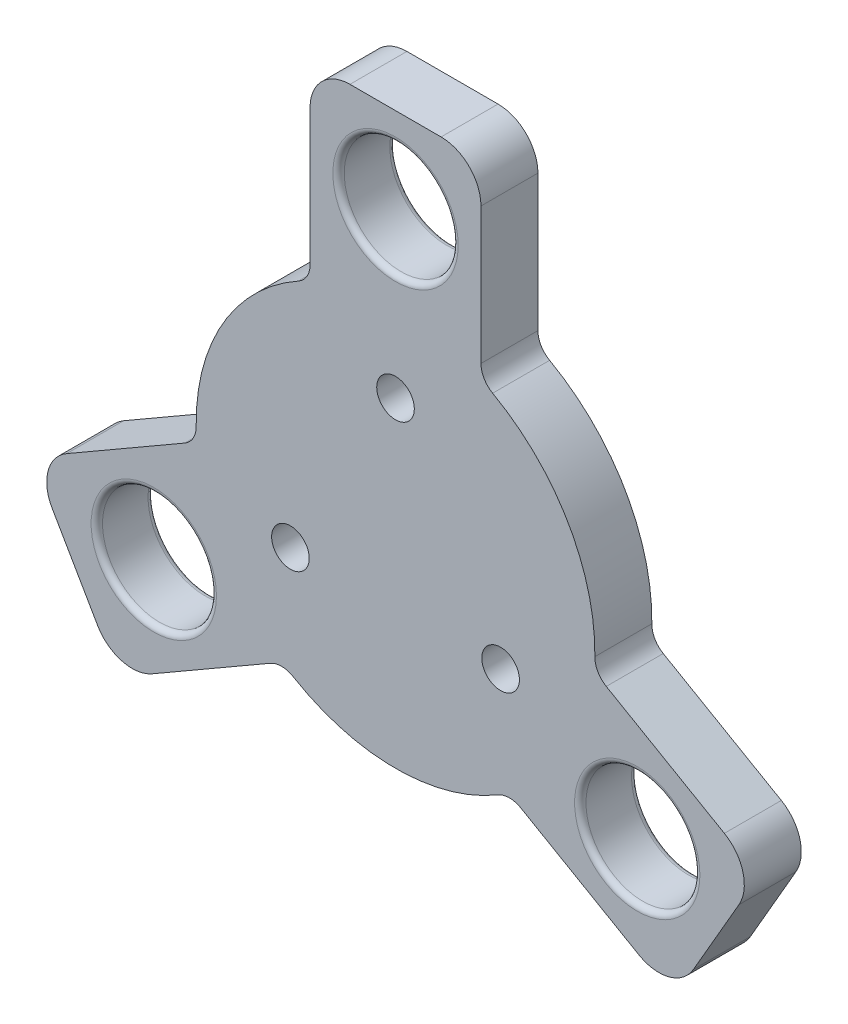
SolidWorks part; units mm, degrees
ref_plane "Front Plane" through (0, 0, 0) normal (0, 0, 1) x (1, 0, 0)
ref_plane "Top Plane" through (0, 0, 0) normal (0, 1, 0) x (1, 0, 0)
ref_plane "Right Plane" through (0, 0, 0) normal (1, 0, 0) x (0, 0, -1)
sketch "Sketch1" plane through (0, 0, 0) normal (0, 0, 1) x (1, 0, 0)
  line L0 (0, 17.5) -> (0, 0) construction
  line L1 (0, 0) -> (-15.1554, -8.75) construction
  line L2 (0, 0) -> (15.1554, -8.75) construction
  line L3 (-7.5, 32.5) -> (-7.5, 15.8114)
  line L4 (7.5, 32.5) -> (7.5, 15.8114)
  line L5 (-7.5, 32.5) -> (7.5, 32.5)
  line L6 (31.8958, -9.7548) -> (17.4431, -1.4105)
  line L7 (24.3958, -22.7452) -> (9.9431, -14.4009)
  line L8 (31.8958, -9.7548) -> (24.3958, -22.7452)
  line L9 (-31.8958, -9.7548) -> (-17.4431, -1.4105)
  line L10 (-24.3958, -22.7452) -> (-9.9431, -14.4009)
  line L11 (-31.8958, -9.7548) -> (-24.3958, -22.7452)
  line L12 (-21.2176, -12.25) -> (-28.1458, -16.25) construction
  line L13 (21.2176, -12.25) -> (28.1458, -16.25) construction
  line L14 (0, 25) -> (0, 30) construction
  line L15 (0, 30) -> (0, 32.5) construction
  circle A0 centre (0, 0) radius 17.5
  circle A1 centre (-21.2176, -12.25) radius 5
  circle A2 centre (21.2176, -12.25) radius 5
  circle A3 centre (0, 25) radius 5
  circle A4 centre (0, 0) radius 2.4
  dimension "D1" = 35
  dimension "D10" = 10
  dimension "D11" = 4.8
  dimension "D2" = 120
  dimension "D3" = 120
  dimension "D4" = 15
  dimension "D5" = 15
  dimension "D12" = 2.5
  dimension "D13" = 8
extrude "Boss-Extrude1" add sketch "Sketch1" along normal blind 5 contours A0 L9 L11 L10 A1 | A0 A4 | A0 L7 L8 L6 A2 | A0 L4 L5 L3 A3 | A4
fillet "Fillet1" radius 3.5 6 edges at (24.3958, -22.7452, 2.5) (31.8958, -9.7548, 2.5) (7.5, 32.5, 2.5) (-7.5, 32.5, 2.5) (-31.8958, -9.7548, 2.5) (-24.3958, -22.7452, 2.5)
fillet "Fillet2" radius 2 6 edges at (-17.4431, -1.4105, 2.5) (-7.5, 15.8114, 2.5) (17.4431, -1.4105, 2.5) (7.5, 15.8114, 2.5) (-9.9431, -14.4009, 2.5) (9.9431, -14.4009, 2.5)
fillet "Fillet3" radius 0.5 6 edges at (-16.2176, -12.25, 5) (-16.2176, -12.25, 0) (26.2176, -12.25, 5) (26.2176, -12.25, 0) (5, 25, 5) (5, 25, 0)
sketch "Sketch2" plane through (0, 0, 5) normal (0, 0, 1) x (1, 0, 0)
  line L0 (0, 0) -> (0, -4.6188) construction
  line L1 (0, -4.6188) -> (4, -2.3094)
  line L2 (4, -2.3094) -> (4, 2.3094)
  line L3 (4, 2.3094) -> (0, 4.6188)
  line L4 (0, 4.6188) -> (-4, 2.3094)
  line L5 (-4, 2.3094) -> (-4, -2.3094)
  line L6 (-4, -2.3094) -> (0, -4.6188)
  circle A0 centre (0, 0) radius 4 construction
  circle A1 centre (0, 0) radius 5.5
  dimension "D2" = 11
  dimension "D1" = 8
extrude "Boss-Extrude2" [suppressed] add sketch "Sketch2" along normal blind 3.15
fillet "Fillet4" [suppressed] radius 3
sketch "Sketch3" plane through (0, 0, 0) normal (0, 0, -1) x (-1, 0, 0)
  line L0 (0, 32.5) -> (0, -17.5) construction
  line L1 (4, 32.5) -> (-4, 32.5) construction
  line L2 (-28.1458, -16.25) -> (15.1554, 8.75) construction
  line L3 (-30.1458, -12.7859) -> (-26.1458, -19.7141) construction
  line L4 (28.1458, -16.25) -> (-15.1554, 8.75) construction
  line L5 (30.1458, -12.7859) -> (26.1458, -19.7141) construction
  arc A0 (-8.9725, -15.0248) -> (8.9725, -15.0248) centre (0, 0) ccw construction
  arc A1 (17.4981, -0.258) -> (8.5256, 15.2828) centre (0, 0) ccw construction
  arc A2 (-8.5256, 15.2828) -> (-17.4981, -0.258) centre (0, 0) ccw construction
  circle A3 centre (0, 0) radius 9 construction
  circle A4 centre (-9.2232, -5.325) radius 1.65
  circle A5 centre (9.2232, -5.325) radius 1.65
  circle A6 centre (0, 10.65) radius 1.65
  dimension "D1" = 18
  dimension "D2" = 3.3
extrude "Cut-Extrude1" cut sketch "Sketch3" against normal up to surface (5 mm away) up to face at (-15.7176, -12.25, 5)
sketch "Sketch4" plane through (0, 0, 5) normal (0, 0, 1) x (1, 0, 0)
  circle A0 centre (-9.2232, -5.325) radius 3
  circle A1 centre (9.2232, -5.325) radius 3
  circle A2 centre (0, 10.65) radius 3
  dimension "D1" = 6
extrude "Cut-Extrude2" [suppressed] cut sketch "Sketch4" along normal up to surface (3.15 mm away)
